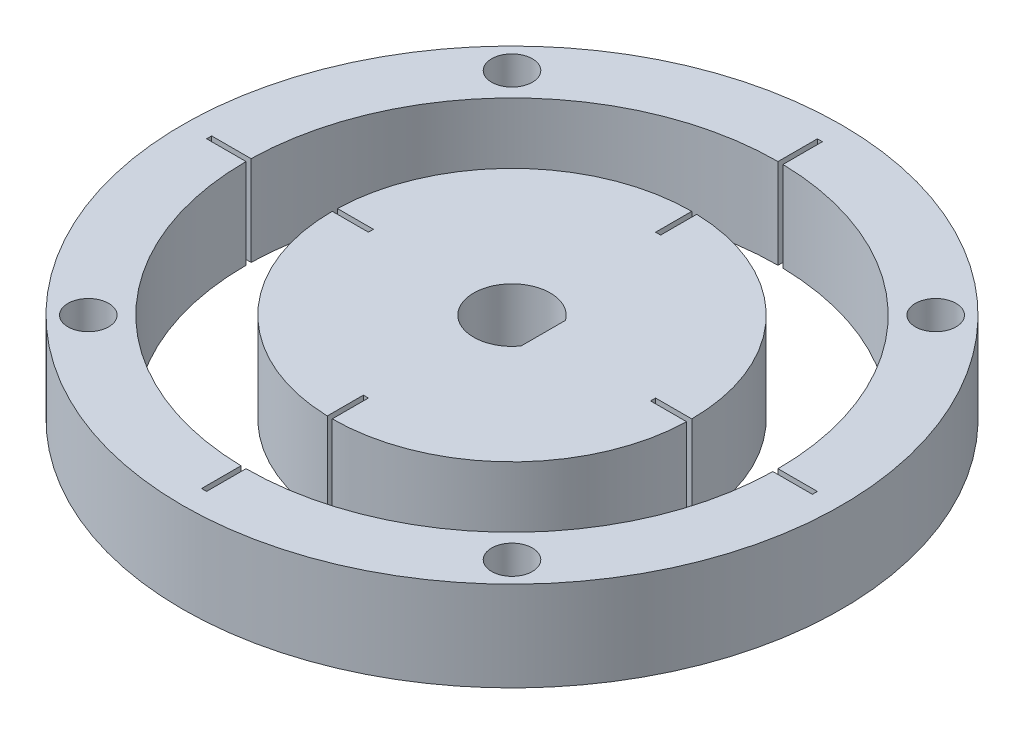
SolidWorks part; units mm, degrees
ref_plane "Front Plane" through (0, 0, 0) normal (0, 0, 1) x (1, 0, 0)
ref_plane "Top Plane" through (0, 0, 0) normal (0, 1, 0) x (1, 0, 0)
ref_plane "Right Plane" through (0, 0, 0) normal (1, 0, 0) x (0, 0, -1)
sketch "Sketch2" plane through (0, 0, 0) normal (0, 1, 0) x (1, 0, 0)
  line L0 (0, -15) -> (0, -11.9832)
  line L1 (0, -11.9832) -> (-0.175, -11.9832)
  line L2 (-15, 0) -> (-11.9832, 0)
  line L3 (0, -11.9832) -> (-0.42, -11.9832)
  line L4 (-0.42, -11.9832) -> (-0.42, -14.9941)
  line L5 (-11.9832, 0.42) -> (-14.9941, 0.42)
  line L6 (-11.9832, 0) -> (-11.9832, 0.42)
  line L7 (0, 15) -> (0, 11.9832)
  line L8 (0.42, 11.9832) -> (0.42, 14.9941)
  line L9 (0, 11.9832) -> (0.42, 11.9832)
  line L10 (15, 0) -> (11.9832, 0)
  line L11 (11.9832, -0.42) -> (14.9941, -0.42)
  line L12 (11.9832, 0) -> (11.9832, -0.42)
  arc A0 (0, -15) -> (14.9941, -0.42) centre (0, 0) ccw
  arc A1 (-0.42, -14.9941) -> (0, -15) centre (0, 0) ccw construction
  arc A2 (-15, 0) -> (-0.42, -14.9941) centre (0, 0) ccw
  arc A3 (-14.9941, 0.42) -> (-15, 0) centre (0, 0) ccw construction
  arc A4 (0, 15) -> (-14.9941, 0.42) centre (0, 0) ccw
  arc A5 (0.42, 14.9941) -> (0, 15) centre (0, 0) ccw construction
  arc A6 (15, 0) -> (0.42, 14.9941) centre (0, 0) ccw
  arc A7 (14.9941, -0.42) -> (15, 0) centre (0, 0) ccw construction
  circle A8 centre (0, 0) radius 22.1975
  circle A9 centre (0, 0) radius 27.5
  point P22 (0, 0)
  dimension "D1" = 30
  dimension "D3" = 55
  dimension "D2" = 4
  dimension "D4" = 0.42
extrude "Boss-Extrude3" add sketch "Sketch2" along normal blind 7.5 contours L0 A0 L11 L12 L10 A6 L8 L9 L7 A4 L5 L6 L2 A2 L4 L3 | A8 | A9
sketch "Sketch4" plane through (0, 7.5, 0) normal (0, 1, 0) x (1, 0, 0)
  circle A0 centre (0, 0) radius 27.5
  dimension "D1" = 55
sketch "Sketch5" plane through (0, 0, 0) normal (0, -1, 0) x (1, 0, 0)
  line L0 (0, -11.9832) -> (0, -25.4832)
  line L1 (0.42, -11.9832) -> (0.42, -25.4832)
  line L2 (0, -25.4832) -> (0.42, -25.4832)
  line L3 (-25.4832, 0) -> (-25.4832, -0.42)
  line L4 (-11.9832, -0.42) -> (-25.4832, -0.42)
  line L5 (-11.9832, 0) -> (-25.4832, 0)
  line L6 (0, 25.4832) -> (-0.42, 25.4832)
  line L7 (-0.42, 11.9832) -> (-0.42, 25.4832)
  line L8 (0, 11.9832) -> (0, 25.4832)
  line L9 (25.4832, 0) -> (25.4832, 0.42)
  line L10 (11.9832, 0.42) -> (25.4832, 0.42)
  line L11 (11.9832, 0) -> (25.4832, 0)
  line L12 (0, -11.9832) -> (0.42, -11.9832)
  line L13 (11.9832, 0.42) -> (11.9832, 0)
  line L14 (-11.9832, 0) -> (-11.9832, -0.42)
  line L15 (-0.42, 11.9832) -> (0, 11.9832)
  circle A0 centre (-17.6777, 17.6777) radius 1.7
  circle A1 centre (17.6777, 17.6777) radius 1.7
  circle A2 centre (17.6777, -17.6777) radius 1.7
  circle A3 centre (-17.6777, -17.6777) radius 1.7
  point P22 (0, 0)
  point P28 (0, 0)
  point P36 (0, 0)
  dimension "D3" = 3.4
  dimension "D2" = 13.5
  dimension "D1" = 4
  dimension "D5" = 4
sketch "Sketch7" plane through (0, 0, 0) normal (0, -1, 0) x (1, 0, 0)
  line L0 (2.611, 1.85) -> (2.611, -1.85)
  arc A0 (2.611, 1.85) -> (2.611, -1.85) centre (0, 0) ccw
  arc A1 (2.611, -1.85) -> (2.611, 1.85) centre (0, 0) ccw construction
  dimension "D1" = 6.4
extrude "Cut-Extrude6" cut sketch "Sketch5" against normal through all contours L0 L2 L1 L12 | L5 L3 L4 L14 | A0 | L7 L6 L8 L15 | A1 | L11 L9 L10 L13 | A2 | A3
extrude "Cut-Extrude8" cut sketch "Sketch7" against normal blind 7.5 contours A0 L0
